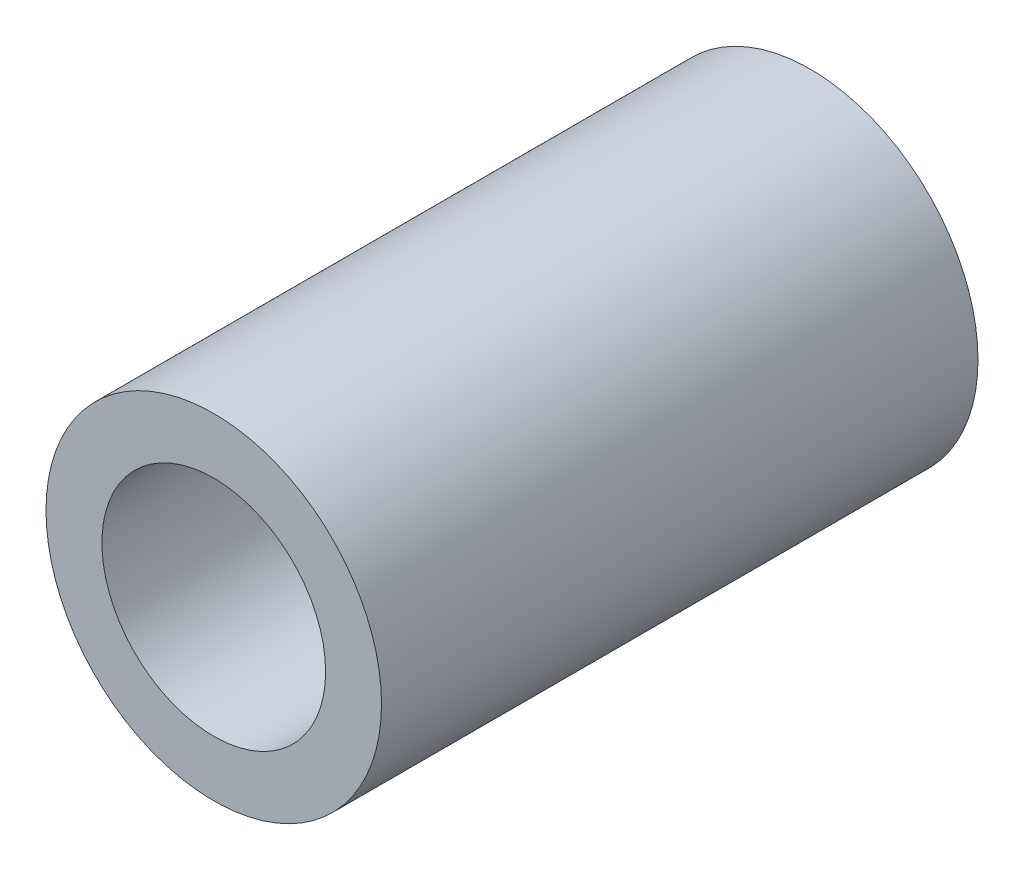
SolidWorks part; units mm, degrees
ref_plane "Front Plane" through (0, 0, 0) normal (0, 0, 1) x (1, 0, 0)
ref_plane "Top Plane" through (0, 0, 0) normal (0, 1, 0) x (1, 0, 0)
ref_plane "Right Plane" through (0, 0, 0) normal (1, 0, 0) x (0, 0, -1)
sketch "Sketch1" plane through (0, 0, 0) normal (0, 0, 1) x (1, 0, 0)
  circle A0 centre (0, 0) radius 3
  circle A1 centre (0, 0) radius 4.5
  dimension "D1" = 6
  dimension "D2" = 9
extrude "Boss-Extrude1" add sketch "Sketch1" along normal blind 16
